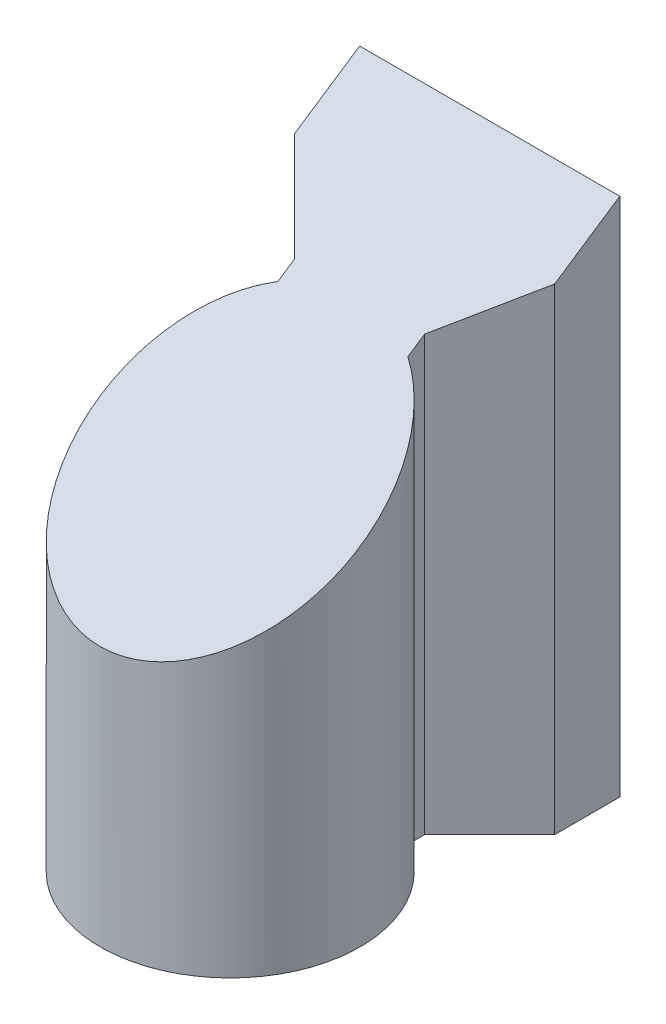
SolidWorks part; units mm, degrees
ref_plane "前视基准面" through (0, 0, 0) normal (0, 0, 1) x (1, 0, 0)
ref_plane "上视基准面" through (0, 0, 0) normal (0, 1, 0) x (1, 0, 0)
ref_plane "右视基准面" through (0, 0, 0) normal (1, 0, 0) x (0, 0, -1)
other "Configuration Table"
sketch "草图1" plane through (0, 0, 0) normal (0, 1, 0) x (1, 0, 0)
  line L3 (0, 19.95) -> (10, 19.95)
  line L4 (0, 19.95) -> (-10, 19.95)
  line L5 (10, 19.95) -> (10, 14.95)
  line L6 (-10, 19.95) -> (-10, 14.95)
  line L10 (-5, 9.9473) -> (-10, 14.95)
  line L13 (5, 9.9473) -> (10, 14.95)
  line L14 (-5, 9.9473) -> (-5, 8.6603)
  line L16 (5, 9.9473) -> (5, 8.6603)
  arc A2 (-5, 8.6603) -> (5, 8.6603) centre (0, 0) ccw
  point P6 (-4.1488, 9.0988)
  point P12 (4.1488, 9.0988)
  dimension "D1" = 19.95
  dimension "D2" = 10
  dimension "D3" = 10
  dimension "D4" = 5
  dimension "D5" = 5
extrude "凸台-拉伸1" add sketch "草图1" along normal blind 40
sketch "草图3" plane through (-10, 0, 0) normal (-1, 0, 0) x (0, 0, 1)
  line L1 (10, 0) -> (10, 40) construction
  line L2 (10, 20) -> (-19.95, 40)
  line L3 (-19.95, 40) -> (10, 40)
  line L4 (10, 40) -> (10, 20)
extrude "切除-拉伸1" cut sketch "草图3" against normal blind 40
